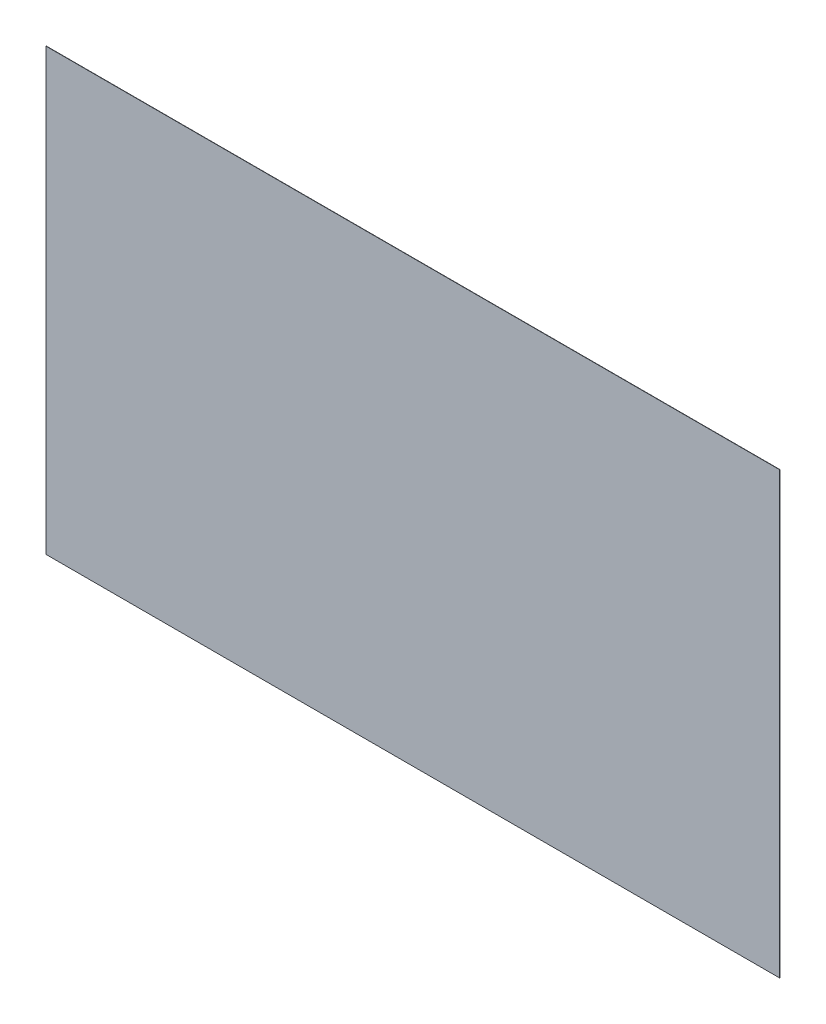
SolidWorks part; units mm, degrees
ref_plane "Front Plane" through (0, 0, 0) normal (0, 0, 1) x (1, 0, 0)
ref_plane "Top Plane" through (0, 0, 0) normal (0, 1, 0) x (1, 0, 0)
ref_plane "Right Plane" through (0, 0, 0) normal (1, 0, 0) x (0, 0, -1)
sketch "Sketch1" plane through (0, 0, 0) normal (0, 0, 1) x (1, 0, 0)
  line L1 (-2500, 1500) -> (2500, 1500)
  line L2 (-2500, 1500) -> (-2500, -1500)
  line L3 (-2500, -1500) -> (2500, -1500)
  line L4 (2500, 1500) -> (2500, -1500)
  line L5 (-2500, 1500) -> (2500, -1500) construction
  line L6 (-2500, -1500) -> (2500, 1500) construction
  point P0 (0, 0)
  dimension "D1" = 3000
  dimension "D2" = 5000
extrude "Boss-Extrude1" add sketch "Sketch1" along normal blind 2
